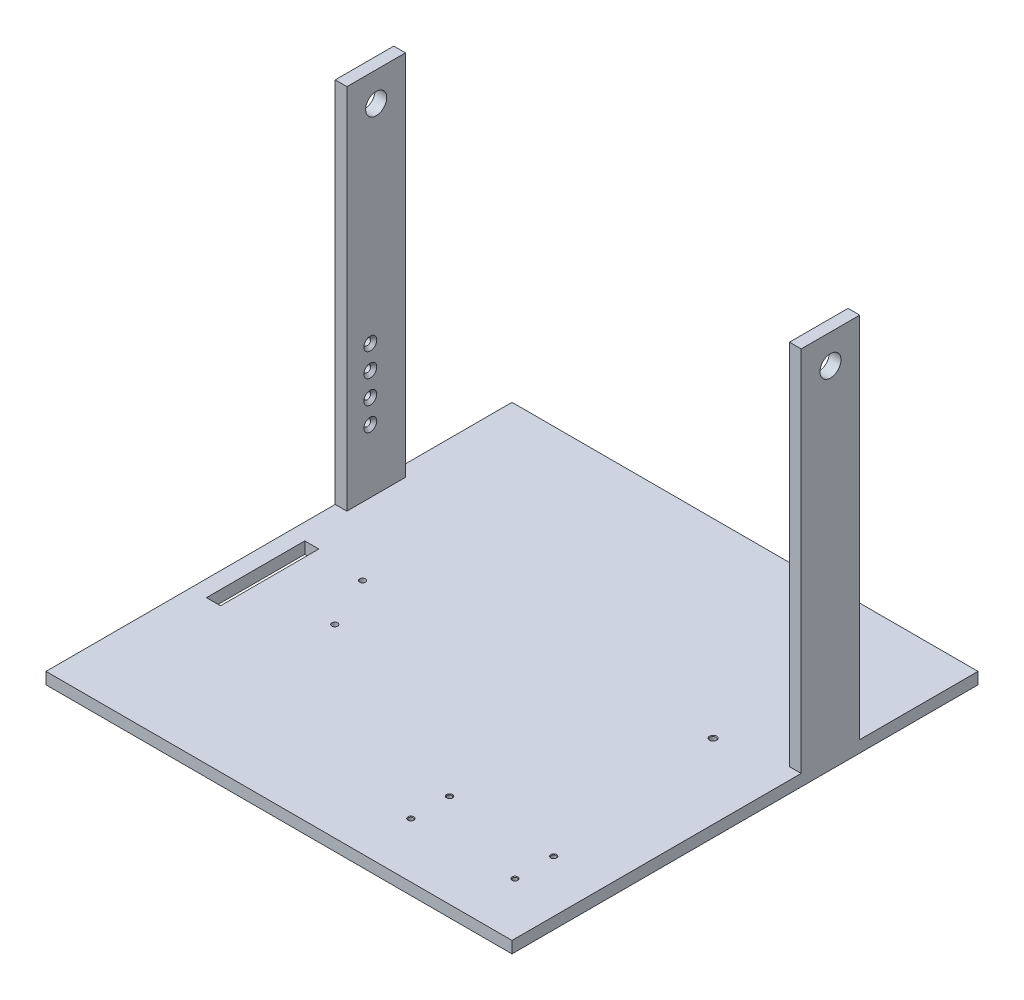
SolidWorks part; units mm, degrees
material "AISI 316 Stainless Steel Sheet (SS)"
ref_plane "Front Plane" through (0, 0, 0) normal (0, 0, 1) x (1, 0, 0)
ref_plane "Top Plane" through (0, 0, 0) normal (0, 1, 0) x (1, 0, 0)
ref_plane "Right Plane" through (0, 0, 0) normal (1, 0, 0) x (0, 0, -1)
sketch "Sketch1" plane through (0, 0, 0) normal (0, 1, 0) x (1, 0, 0)
  line L0 (0, 0) -> (199, 0)
  line L1 (199, 0) -> (199, -199)
  line L2 (199, -199) -> (0, -199)
  line L3 (0, -199) -> (0, 0)
  dimension "D1" = 199
  dimension "D2" = 199
extrude "Boss-Extrude1" add sketch "Sketch1" along normal blind 5
sketch "Sketch2" plane through (0, 5, 0) normal (0, 1, 0) x (1, 0, 0)
  line L0 (0, -50.5) -> (0, -75.5)
  line L1 (0, 0) -> (0, -199) construction
  line L2 (0, -75.5) -> (5, -75.5)
  line L3 (5, -75.5) -> (5, -50.5)
  line L4 (5, -50.5) -> (0, -50.5)
  dimension "D1" = 25
  dimension "D2" = 50.5
  dimension "D3" = 5
extrude "Boss-Extrude2" add sketch "Sketch2" along normal blind 18.8
sketch "Sketch3" plane through (0, 23.8, 0) normal (0, 1, 0) x (1, 0, 0)
  line L0 (5, -50.5) -> (5, -75.5)
  line L1 (5, -75.5) -> (5, -50.5) construction
  line L2 (5, -50.5) -> (0, -50.5) construction
  line L3 (5, -75.5) -> (0, -75.5)
  line L5 (0, -75.5) -> (0, -50.5)
  line L6 (0, -50.5) -> (5, -50.5)
  dimension "D1" = 25
extrude "Boss-Extrude3" add sketch "Sketch3" along normal blind 46.4
sketch "Sketch4" plane through (0, 70.2, 0) normal (0, 1, 0) x (1, 0, 0)
  line L0 (0, -50.5) -> (5, -50.5)
  line L1 (0, -50.5) -> (0, -75.5)
  line L2 (5, -50.5) -> (5, -75.5)
  line L3 (0, -75.5) -> (5, -75.5)
  line L4 (0, -50.5) -> (0, -75.5) construction
  line L5 (5, -50.5) -> (0, -50.5) construction
  line L6 (5, -75.5) -> (5, -50.5) construction
  dimension "D1" = 25
extrude "Boss-Extrude4" add sketch "Sketch4" along normal blind 91.8
sketch "Sketch5" plane through (0, 5, 0) normal (0, 1, 0) x (1, 0, 0)
  line L0 (199, -50.5) -> (194, -50.5)
  line L1 (199, -199) -> (199, 0) construction
  line L2 (194, -50.5) -> (194, -75.5)
  line L3 (194, -75.5) -> (199, -75.5)
  line L4 (199, -75.5) -> (199, -50.5)
  line L5 (5, -50.5) -> (0, -50.5) construction
  line L6 (0, -75.5) -> (5, -75.5) construction
  dimension "D1" = 5
extrude "Boss-Extrude5" add sketch "Sketch5" along normal blind 157
sketch "Sketch6" plane through (0, 0, 0) normal (-1, 0, 0) x (0, 0, 1)
  line L0 (75.5, 162) -> (75.5, 5) construction
  line L1 (50.5, 162) -> (75.5, 162) construction
  circle A0 centre (63, 149.5) radius 4.5
  dimension "D3" = 9
  dimension "D1" = 12.5
  dimension "D2" = 12.5
extrude "Cut-Extrude1" cut sketch "Sketch6" against normal through all
sketch "Sketch12" plane through (0, 5, 0) normal (0, 1, 0) x (1, 0, 0)
  line L0 (7, -95.5) -> (13, -95.5)
  line L1 (13, -95.5) -> (13, -137.5)
  line L2 (13, -137.5) -> (7, -137.5)
  line L3 (7, -137.5) -> (7, -95.5)
  line L4 (0, -75.5) -> (0, -199) construction
  line L5 (199, 0) -> (0, 0) construction
  dimension "D1" = 7
  dimension "D2" = 13
  dimension "D3" = 42
  dimension "D4" = 95.5
extrude "Cut-Extrude3" cut sketch "Sketch12" against normal blind 5
sketch "Sketch14" plane through (0, 5, 0) normal (0, 1, 0) x (1, 0, 0)
  line L0 (13, -137.5) -> (13, -95.5) construction
  circle A0 centre (34, -97.8) radius 1.25
  circle A1 centre (44.3188, -120) radius 1.25
  point P6 (13, -116.5)
  dimension "D1" = 2.5
  dimension "D2" = 2.5
  dimension "D3" = 21
  dimension "D4" = 18.7
  dimension "D5" = 3.5
  dimension "D6" = 10.3187
hole_wizard "M3x0.5 Tapped Hole1" positions "Sketch18" profile "Sketch19" tap size "M3x0.5" standard "ANSI Metric"
sketch "Sketch18" plane through (0, 5, 0) normal (0, 1, 0) x (1, 0, 0)
  point P0 (34, -97.8)
  point P3 (44.3188, -120)
sketch "Sketch19" plane through (34, 5, 97.8) normal (1, 0, 0) x (0, 0, 1)
  line L0 (0, 0) -> (0, 4.7511)
  line L1 (0, 4.7511) -> (1.25, 4)
  line L2 (1.25, 4) -> (1.25, 0)
  line L5 (1.25, 0) -> (0, 0)
  line L10 (0, 4.7511) -> (-1.25, 4) construction
  line L11 (0, -6.35) -> (0, 107.95) construction
  dimension "Tap Drill Dia." = 2.5
  dimension "Tap Drill Depth" = 4
  dimension "Drill Angle" = 118
cosmetic thread "Hole Thread1" parameters "D1"=3.5, "D2"=3
cosmetic thread "Hole Thread2" parameters "D1"=3.5, "D2"=3
sketch "Sketch21" plane through (5, 0, 0) normal (1, 0, 0) x (0, 0, -1)
  line L0 (-75.5, 162) -> (-75.5, 5) construction
  line L1 (-68, 70.2) -> (-63, 70.2)
  line L2 (-68, 70.2) -> (-68, 23.8)
  line L3 (-68, 23.8) -> (-63, 23.8)
  line L4 (-63, 70.2) -> (-63, 23.8)
  line L5 (-199, 0) -> (0, 0) construction
  line L6 (-65.5, 70.2) -> (-65.5, 23.8) construction
  line L7 (-68, 32) -> (-63, 32) construction
  line L8 (-68, 27) -> (-63, 27) construction
  line L9 (-68, 37) -> (-63, 37) construction
  line L10 (-68, 42) -> (-63, 42) construction
  line L11 (-68, 47) -> (-63, 47) construction
  line L12 (-68, 52) -> (-63, 52) construction
  line L13 (-68, 57) -> (-63, 57) construction
  line L14 (-68, 62) -> (-63, 62) construction
  line L15 (-68, 67) -> (-63, 67) construction
  line L16 (-68, 27) -> (-68, 32) construction
  point P10 (-65.5, 62)
  point P11 (-65.5, 52)
  point P32 (-65.5, 42)
  point P33 (-65.5, 32)
  dimension "D1" = 7.5
  dimension "D2" = 23.8
  dimension "D3" = 5
  dimension "D4" = 46.4
  dimension "D5" = 9
  dimension "D6" = 3.2
  dimension "D7" = 5
hole_wizard "CSK for M2.5 Flat Head Machine Screw1" positions "3DSketch1" profile "Sketch22" countersink size "M2.5" standard "ANSI Metric"
sketch3d "3DSketch1"
  point P0 (5, 62, 65.5)
  point P3 (5, 52, 65.5)
  point P6 (5, 42, 65.5)
  point P9 (5, 32, 65.5)
sketch "Sketch22" plane through (5, 62, 65.5) normal (0, 1, 0) x (0, 0, -1)
  line L0 (0, 0) -> (0, 5)
  line L1 (0, 5) -> (1.45, 5)
  line L2 (1.45, 5) -> (1.45, 1.3)
  line L3 (1.45, 1.3) -> (2.75, 0)
  line L5 (2.75, 0) -> (0, 0)
  line L6 (-1.45, 1.3) -> (-2.75, 0) construction
  line L11 (0, -6.35) -> (0, 107.95) construction
  dimension "Thru Hole Dia." = 2.9
  dimension "Thru Hole Depth" = 5
  dimension "Near C'Sink Dia." = 5.5
  dimension "Near C'Sink Angle" = 90
sketch "Sketch23" plane through (0, 5, 0) normal (0, 1, 0) x (1, 0, 0)
  line L0 (199, -199) -> (199, -75.5) construction
  line L1 (132.3233, -158.9994) -> (176.7767, -158.9994)
  line L2 (132.3233, -158.9994) -> (132.3233, -175.5006)
  line L3 (132.3233, -175.5006) -> (176.7767, -175.5006)
  line L4 (176.7767, -158.9994) -> (176.7767, -175.5006)
  line L5 (154.55, -175.5006) -> (154.55, -158.9994) construction
  line L6 (132.3233, -167.25) -> (176.7767, -167.25) construction
  line L7 (0, -199) -> (199, -199) construction
  point P220 (154.55, -167.25)
  dimension "D1" = 22.2233
  dimension "D2" = 23.4994
  dimension "D3" = 44.4534
  dimension "D4" = 16.5013
hole_wizard "M2.5x0.45 Tapped Hole1" positions "Sketch24" profile "Sketch25" tap size "M2.5x0.45" standard "ANSI Metric"
sketch "Sketch24" plane through (0, 5, 0) normal (0, 1, 0) x (1, 0, 0)
  point P0 (132.3233, -175.5006)
  point P2 (132.3233, -158.9994)
  point P4 (176.7767, -158.9994)
  point P6 (176.7767, -175.5006)
sketch "Sketch25" plane through (132.3233, 5, 175.5006) normal (1, 0, 0) x (0, 0, 1)
  line L0 (0, 0) -> (0, 4.6159)
  line L1 (0, 4.6159) -> (1.025, 4)
  line L2 (1.025, 4) -> (1.025, 0.25)
  line L3 (1.025, 0.25) -> (1.275, 0)
  line L5 (1.275, 0) -> (0, 0)
  line L6 (-1.025, 0.25) -> (-1.275, 0) construction
  line L10 (0, 4.6159) -> (-1.025, 4) construction
  line L11 (0, -6.35) -> (0, 107.95) construction
  dimension "Tap Drill Dia." = 2.05
  dimension "Tap Drill Depth" = 4
  dimension "Near C'Sink Dia." = 2.55
  dimension "Near C'Sink Angle" = 90
  dimension "Drill Angle" = 118
cosmetic thread "Hole Thread3" parameters "D1"=3.5, "D2"=2.5
cosmetic thread "Hole Thread4" parameters "D1"=3.5, "D2"=2.5
cosmetic thread "Hole Thread5" parameters "D1"=3.5, "D2"=2.5
cosmetic thread "Hole Thread6" parameters "D1"=3.5, "D2"=2.5
sketch "Sketch26" plane through (0, 5, 0) normal (0, 1, 0) x (1, 0, 0)
  line L0 (199, -199) -> (199, -75.5) construction
  line L1 (199, 0) -> (0, 0) construction
  point P0 (167.156, -81.28)
  dimension "D1" = 31.844
  dimension "D2" = 81.28
hole_wizard "M3x0.5 Tapped Hole2" positions "Sketch27" profile "Sketch28" tap size "M3x0.5" standard "ANSI Metric"
sketch "Sketch27" plane through (0, 5, 0) normal (0, 1, 0) x (1, 0, 0)
  point P0 (167.156, -81.28)
sketch "Sketch28" plane through (167.156, 5, 81.28) normal (1, 0, 0) x (0, 0, 1)
  line L0 (0, 0) -> (0, 5.0511)
  line L1 (0, 5.0511) -> (1.25, 4.3)
  line L2 (1.25, 4.3) -> (1.25, 0.275)
  line L3 (1.25, 0.275) -> (1.525, 0)
  line L5 (1.525, 0) -> (0, 0)
  line L6 (-1.25, 0.275) -> (-1.525, 0) construction
  line L10 (0, 5.0511) -> (-1.25, 4.3) construction
  line L11 (0, -6.35) -> (0, 107.95) construction
  dimension "Tap Drill Dia." = 2.5
  dimension "Tap Drill Depth" = 4.3
  dimension "Near C'Sink Dia." = 3.05
  dimension "Near C'Sink Angle" = 90
  dimension "Drill Angle" = 118
cosmetic thread "Hole Thread7" parameters "D1"=4, "D2"=3
